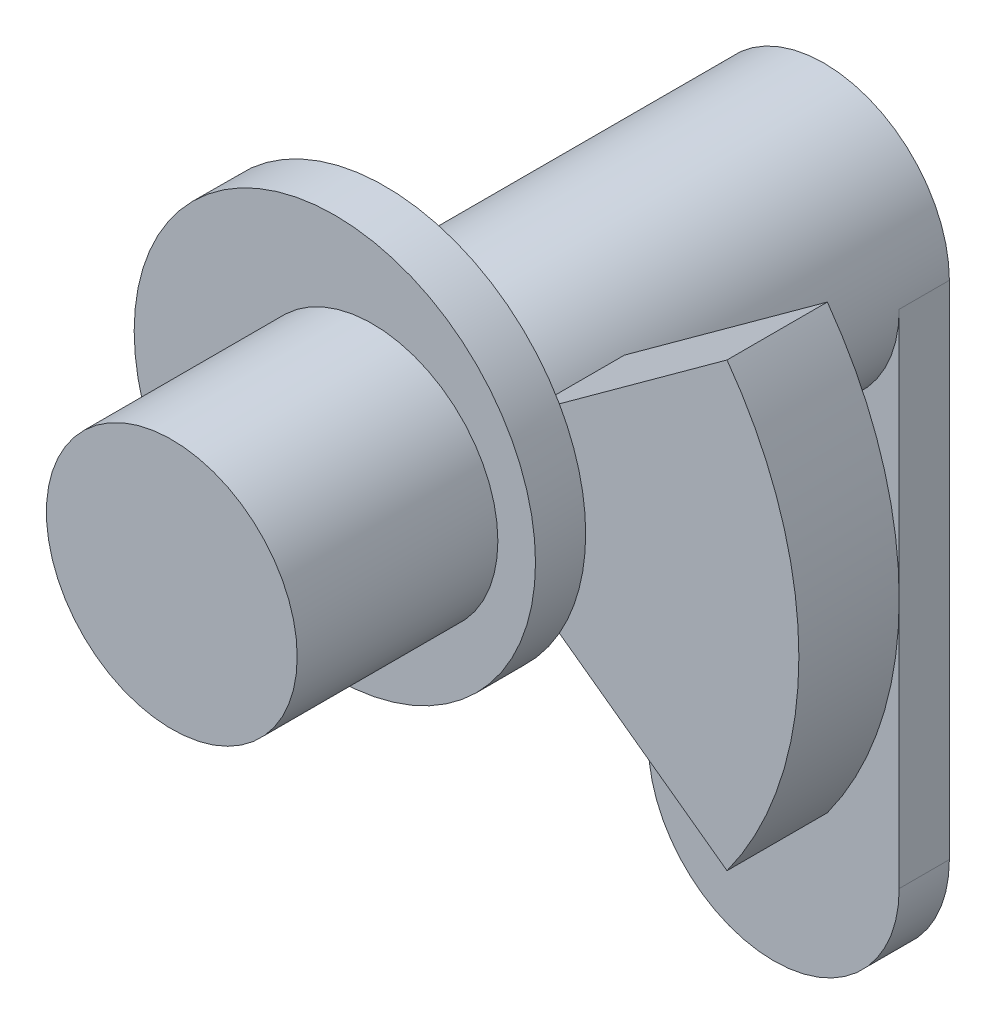
SolidWorks part; units mm, degrees
ref_plane "Front Plane" through (0, 0, 0) normal (0, 0, 1) x (1, 0, 0)
ref_plane "Top Plane" through (0, 0, 0) normal (0, 1, 0) x (1, 0, 0)
ref_plane "Right Plane" through (0, 0, 0) normal (1, 0, 0) x (0, 0, -1)
sketch "Sketch1" plane through (0, 0, 0) normal (0, 0, 1) x (1, 0, 0)
  circle A0 centre (0, 0) radius 63.5
  dimension "D1" = 127
extrude "Boss-Extrude1" add sketch "Sketch1" along normal blind 330.2
sketch "Sketch2" plane through (0, 0, 0) normal (0, 0, -1) x (-1, 0, 0)
  line L0 (63.5, 0) -> (63.5, -254)
  line L1 (-63.5, 0) -> (-63.5, -254)
  circle A0 centre (0, 0) radius 63.5 construction
  arc A1 (-63.5, -254) -> (63.5, -254) centre (0, -254) ccw
  arc A2 (63.5, 0) -> (-63.5, 0) centre (0, 0) ccw
  dimension "D3" = 63.5
  dimension "D1" = 254
  dimension "D2" = 254
extrude "Boss-Extrude2" add sketch "Sketch2" against normal blind 25.4
ref_plane "Plane1" through (0, 0, 228.6) normal (0, 0, 1) x (1, 0, 0)
sketch "Sketch3" plane through (0, 0, 228.6) normal (0, 0, 1) x (1, 0, 0)
  line L0 (0, 0) -> (-19.05, 0) construction
  circle A1 centre (-19.05, 0) radius 101.6
  dimension "D2" = 203.2
  dimension "D1" = 19.05
extrude "Boss-Extrude3" add sketch "Sketch3" against normal blind 25.4
ref_plane "Plane2" through (0, 0, 203.2) normal (0, 0, 1) x (1, 0, 0)
sketch "Sketch5" plane through (0, 0, 203.2) normal (0, 0, 1) x (1, 0, 0)
  line L2 (0, 0) -> (154.1177, 111.9731)
  line L3 (0, 0) -> (154.1177, -111.9731)
  arc A0 (154.1177, -111.9731) -> (154.1177, 111.9731) centre (0, 0) ccw
  point P11 (46.1677, 0)
  dimension "D1" = 381
  dimension "D2" = 107.95
extrude "Boss-Extrude4" add sketch "Sketch5" against normal blind 50.8
